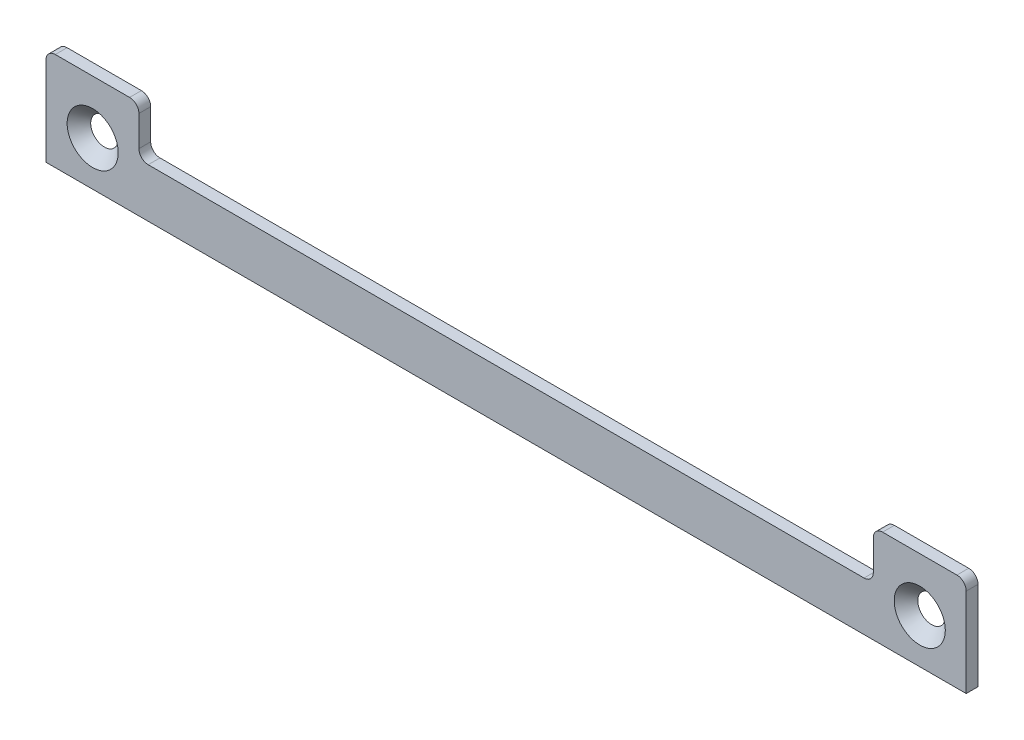
SolidWorks part; units mm, degrees
material "7075-T6, Plate (SS)"
ref_plane "Front Plane" through (0, 0, 0) normal (0, 0, 1) x (1, 0, 0)
ref_plane "Top Plane" through (0, 0, 0) normal (0, 1, 0) x (1, 0, 0)
ref_plane "Right Plane" through (0, 0, 0) normal (1, 0, 0) x (0, 0, -1)
sketch "Sketch1" plane through (0, 0, 0) normal (0, 0, 1) x (1, 0, 0)
  line L0 (-38.5, 0) -> (60.56, 0)
  line L1 (60.56, 0) -> (60.56, 10.5509)
  line L2 (60.56, 10.5509) -> (50.56, 10.5509)
  line L3 (50.56, 10.5509) -> (50.56, 5.2754)
  line L4 (50.56, 5.2754) -> (-28.5, 5.2754)
  line L5 (-28.5, 5.2754) -> (-28.5, 10.5509)
  line L6 (-28.5, 10.5509) -> (-38.5, 10.5509)
  line L7 (-38.5, 10.5509) -> (-38.5, 0)
  dimension "D1" = 10
  dimension "D2" = 10
  dimension "D3" = 99.06
extrude "Boss-Extrude1" add sketch "Sketch1" along normal blind 1.27
fillet "Fillet1" radius 1 6 edges at (60.56, 10.5509, 0.635) (50.56, 10.5509, 0.635) (50.56, 5.2754, 0.635) (-28.5, 5.2754, 0.635) (-28.5, 10.5509, 0.635) (-38.5, 10.5509, 0.635)
sketch "Sketch4" plane through (0, 0, 1.27) normal (0, 0, 1) x (1, 0, 0)
  line L0 (-33.5, 10.5509) -> (-33.5, 0) construction
  line L1 (-29.5, 10.5509) -> (-37.5, 10.5509) construction
  line L2 (-38.5, 0) -> (60.56, 0) construction
  line L3 (-38.5, 4.7754) -> (-27.7589, 4.7754) construction
  line L4 (-38.5, 9.5509) -> (-38.5, 0) construction
  line L5 (55.56, 10.5509) -> (55.56, 0) construction
  line L6 (59.56, 10.5509) -> (51.56, 10.5509) construction
  line L7 (60.56, 4.7754) -> (50.1539, 4.7754) construction
  line L8 (60.56, 0) -> (60.56, 9.5509) construction
hole_wizard "CSK for M2.5 Countersunk Raised Head Screw1" positions "Sketch5" profile "Sketch6" countersink size "M2.5" standard "ISO" end condition up to next
sketch "Sketch5" plane through (0, 0, 1.27) normal (0, 0, 1) x (1, 0, 0)
  point P0 (-33.4766, 4.7754)
  point P2 (55.5603, 4.7754)
sketch "Sketch6" plane through (-33.4766, 4.7754, 1.27) normal (1, 0, 0) x (0, -1, 0)
  line L0 (0, 0) -> (0, 1.27)
  line L1 (0, 1.27) -> (1.45, 1.27)
  line L2 (1.45, 1.27) -> (1.45, 1.3)
  line L3 (1.45, 1.3) -> (2.75, 0)
  line L5 (2.75, 0) -> (0, 0)
  line L6 (-1.45, 1.3) -> (-2.75, 0) construction
  line L11 (0, -6.35) -> (0, 107.95) construction
  dimension "Thru Hole Dia." = 2.9
  dimension "Thru Hole Depth" = 1.27
  dimension "Near C'Sink Dia." = 5.5
  dimension "Near C'Sink Angle" = 90
